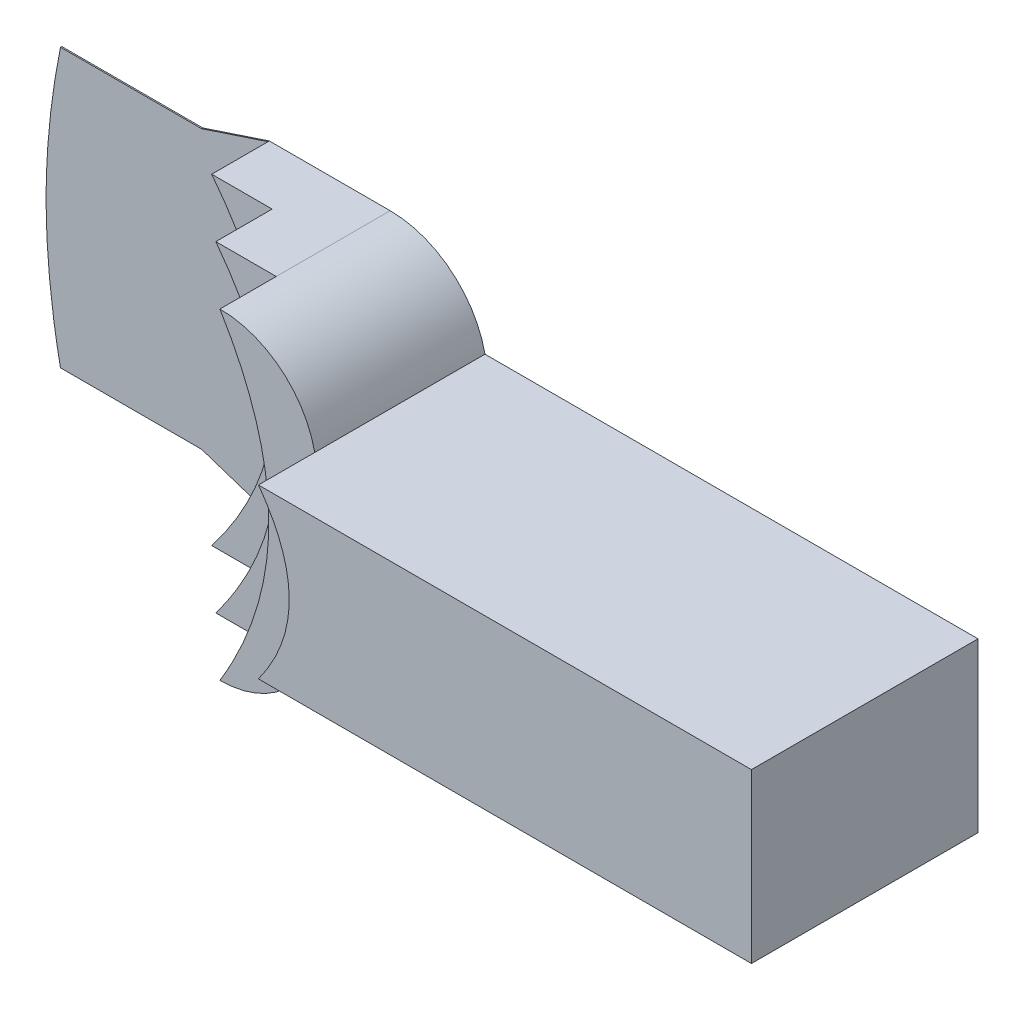
SolidWorks part; units mm, degrees
material "Alliage 1060"
ref_plane "Plan de dessus" through (0, 0, 0) normal (0, 0, 1) x (1, 0, 0)
ref_plane "Plan de droite" through (0, 0, 0) normal (0, 1, 0) x (1, 0, 0)
ref_plane "Plan de face" through (0, 0, 0) normal (1, 0, 0) x (0, 0, -1)
sketch "Esquisse2" plane through (0, 0, 0) normal (0, 0, 1) x (1, 0, 0)
  line L0 (572.6572, -29.6417) -> (7119.055, -29.6417) construction
  line L7 (2720.1635, 521.8378) -> (5784.1635, 521.8378)
  line L31 (0, 3031.3749) -> (6129.05, 3031.3749) construction
  line L33 (-3512.8831, -987.3792) -> (-3389.5498, -987.3792) construction
  line L42 (1379.9521, 999.3511) -> (2130.8584, 999.3511)
  line L43 (1379.9521, 999.3511) -> (966.8758, 862.8508)
  line L52 (2911.396, 0) -> (6237.7744, 0) construction
  line L53 (5784.1635, 521.8378) -> (5784.1635, -521.8378)
  line L54 (966.8758, 862.8508) -> (89.9945, 862.8508)
  line L58 (2720.1635, -521.8378) -> (5784.1635, -521.8378)
  line L59 (1379.9521, -999.3511) -> (966.8758, -862.8508)
  line L60 (1379.9521, -999.3511) -> (2130.8584, -999.3511)
  line L61 (966.8758, -862.8508) -> (89.9945, -862.8508)
  arc A2 (2130.8584, 999.3511) -> (2720.1635, 521.8378) centre (2130.8584, 396.9601) cw
  arc A3 (2130.8584, -999.3511) -> (2720.1635, -521.8378) centre (2130.8584, -396.9601) ccw
  spline S0 degree 2 poles (89.9945, 862.8508) (1.9872, 431.5244) (0, 0) knots 0 0 0 0.48871 0.48871 0.48871
  spline S1 degree 2 poles (89.9945, -862.8508) (1.9872, -431.5244) (0, 0) knots 0 0 0 0.48871 0.48871 0.48871
  point P30 (5784.1635, 0)
  dimension "D3" = 6129.05
  dimension "D4" = 3064
sketch "Esquisse3" plane through (0, 0, 0) normal (0, 0, 1) x (1, 0, 0)
  line L0 (1379.9521, 999.3511) -> (2130.8584, 999.3511)
  line L1 (1379.9521, 999.3511) -> (966.8758, 862.8508)
  line L2 (966.8758, 862.8508) -> (89.9945, 862.8508)
  line L3 (1379.9521, -999.3511) -> (966.8758, -862.8508)
  line L4 (1379.9521, -999.3511) -> (2130.8584, -999.3511)
  line L5 (966.8758, -862.8508) -> (89.9945, -862.8508)
  arc A0 (2130.8584, 999.3511) -> (2720.1635, 521.8378) centre (2130.8584, 396.9601) cw
  arc A1 (2130.8584, -999.3511) -> (2720.1635, -521.8378) centre (2130.8584, -396.9601) ccw
  spline S0 degree 2 poles (89.9945, 862.8508) (1.9872, 431.5244) (0, 0) knots 0 0 0 0.48871 0.48871 0.48871
  spline S1 degree 2 poles (89.9945, -862.8508) (1.9872, -431.5244) (0, 0) knots 0 0 0 0.48871 0.48871 0.48871
  spline S2 degree 2 poles (2720.1635, 521.8378) (3102.6284, 0) (2720.1635, -521.8378) knots 0 0 0 1 1 1
extrude "Boss.-Extru.2" add sketch "Esquisse2" along normal blind 1408
sketch "Esquisse8" plane through (0, 0, 1408) normal (0, 0, 1) x (1, 0, 0)
  arc A1 (2130.8584, -999.3511) -> (2720.1635, -521.8378) centre (2130.8584, -396.9601) ccw construction
  arc A2 (2720.1635, 521.8378) -> (2130.8584, 999.3511) centre (2130.8584, 396.9601) ccw construction
  spline S0 degree 2 poles (2130.8584, 999.3511) (2989.1422, 0) (2130.8584, -999.3511) knots 0 0 0 1 1 1
  spline S1 degree 2 poles (2130.8584, -999.3511) (2594.6909, -969.3815) (2720.1635, -521.8378) knots 0 0 0 1 1 1
  spline S2 degree 2 poles (2720.1635, -521.8378) (3102.6284, 0) (2720.1635, 521.8378) knots 0 0 0 1 1 1
  spline S3 degree 2 poles (2720.1635, 521.8378) (2594.6909, 969.3815) (2130.8584, 999.3511) knots 0 0 0 1 1 1
extrude "Enlèv. mat.-Extru.9" cut sketch "Esquisse3" against normal blind 350 from surface at 1408 starting at face at (2024.092, 66.3731, 1408)
sketch "Esquisse9" plane through (0, 0, 1058) normal (0, 0, 1) x (1, 0, 0)
  line L0 (1379.9521, 999.3511) -> (2130.8584, 999.3511)
  line L1 (1379.9521, 999.3511) -> (966.8758, 862.8508)
  line L2 (966.8758, 862.8508) -> (89.9945, 862.8508)
  line L3 (1379.9521, -999.3511) -> (966.8758, -862.8508)
  line L4 (1379.9521, -999.3511) -> (2130.8584, -999.3511)
  line L5 (966.8758, -862.8508) -> (89.9945, -862.8508)
  line L6 (2130.8584, -999.3511) -> (1379.9521, -999.3511)
  line L7 (966.8758, -862.8508) -> (89.9945, -862.8508)
  line L8 (966.8758, -862.8508) -> (89.9945, -862.8508)
  line L9 (89.9945, 862.8508) -> (966.8758, 862.8508)
  line L10 (1379.9521, 999.3511) -> (2130.8584, 999.3511)
  arc A0 (2130.8584, 999.3511) -> (2720.1635, 521.8378) centre (2130.8584, 396.9601) cw
  arc A1 (2130.8584, -999.3511) -> (2720.1635, -521.8378) centre (2130.8584, -396.9601) ccw
  spline S0 degree 2 poles (89.9945, 862.8508) (1.9872, 431.5244) (0, 0) knots 0 0 0 0.48871 0.48871 0.48871
  spline S1 degree 2 poles (89.9945, -862.8508) (1.9872, -431.5244) (0, 0) knots 0 0 0 0.48871 0.48871 0.48871
  spline S2 degree 2 poles (2720.1635, 521.8378) (3102.6284, 0) (2720.1635, -521.8378) knots 0 0 0 1 1 1
  spline S3 degree 2 poles (2130.8584, 999.3511) (2738.4839, 0) (2130.8584, -999.3511) knots 0 0 0 1 1 1
  spline S4 degree 2 poles (89.9945, -862.8508) (-89.9945, 0) (89.9945, 862.8508) knots 0 0 0 1 1 1
  line M12 (1379.9521, 999.3511) -> (966.8758, 862.8508)
  line M13 (966.8758, 862.8508) -> (89.9945, 862.8508)
  spline M14 degree 2 poles (89.9945, 862.8508) (1.9872, 431.5244) (0, 0) knots 0 0 0 1 1 1
  spline M15 degree 2 poles (0, 0) (1.9872, -431.5244) (89.9945, -862.8508) knots 0 0 0 1 1 1
  line M16 (89.9945, -862.8508) -> (966.8758, -862.8508)
  line M17 (966.8758, -862.8508) -> (1379.9521, -999.3511)
  line M18 (1379.9521, -999.3511) -> (2130.8584, -999.3511)
  line M22 (2130.8584, 999.3511) -> (1379.9521, 999.3511)
extrude "Enlèv. mat.-Extru.10" cut sketch "Esquisse9" against normal blind 350 contours S3 M22 M12 M13 M14 M15 M16 M17 M18
sketch "Esquisse10" plane through (0, 0, 708) normal (0, 0, 1) x (1, 0, 0)
  line L0 (1379.9521, 999.3511) -> (2130.8584, 999.3511)
  line L1 (1379.9521, 999.3511) -> (966.8758, 862.8508)
  line L2 (966.8758, 862.8508) -> (89.9945, 862.8508)
  line L3 (1379.9521, -999.3511) -> (966.8758, -862.8508)
  line L4 (1379.9521, -999.3511) -> (2130.8584, -999.3511)
  line L5 (966.8758, -862.8508) -> (89.9945, -862.8508)
  line L6 (1379.9521, -999.3511) -> (966.8758, -862.8508)
  line L7 (89.9945, 862.8508) -> (966.8758, 862.8508)
  line L8 (2130.8584, 999.3511) -> (1379.9521, 999.3511) construction
  arc A0 (2130.8584, 999.3511) -> (2720.1635, 521.8378) centre (2130.8584, 396.9601) cw
  arc A1 (2130.8584, -999.3511) -> (2720.1635, -521.8378) centre (2130.8584, -396.9601) ccw
  spline S0 degree 2 poles (89.9945, 862.8508) (1.9872, 431.5244) (0, 0) knots 0 0 0 0.48871 0.48871 0.48871
  spline S1 degree 2 poles (89.9945, -862.8508) (1.9872, -431.5244) (0, 0) knots 0 0 0 0.48871 0.48871 0.48871
  spline S2 degree 2 poles (2720.1635, 521.8378) (3102.6284, 0) (2720.1635, -521.8378) knots 0 0 0 1 1 1
  spline S3 degree 2 poles (1755.4053, 999.3511) (2506.3115, 0) (1755.4053, -999.3511) knots 0 0 0 1 1 1
  spline S4 degree 2 poles (89.9945, -862.8508) (-89.9945, 0) (89.9945, 862.8508) knots 0 0 0 1 1 1
extrude "Enlèv. mat.-Extru.11" cut sketch "Esquisse10" against normal blind 350
sketch "Esquisse11" plane through (0, 0, 358) normal (0, 0, 1) x (1, 0, 0)
  line L1 (966.8758, -862.8508) -> (89.9945, -862.8508)
  line L2 (89.9945, 862.8508) -> (966.8758, 862.8508)
  line L3 (966.8758, 862.8508) -> (1379.9521, 999.3511)
  line L4 (1379.9521, -999.3511) -> (966.8758, -862.8508)
  spline S0 degree 2 poles (1379.9521, 999.3511) (2157.5333, 0) (1379.9521, -999.3511) knots 0 0 0 1 1 1
  spline S1 degree 2 poles (89.9945, -862.8508) (-89.9945, 0) (89.9945, 862.8508) knots 0 0 0 1 1 1
extrude "Enlèv. mat.-Extru.12" cut sketch "Esquisse11" against normal blind 350
